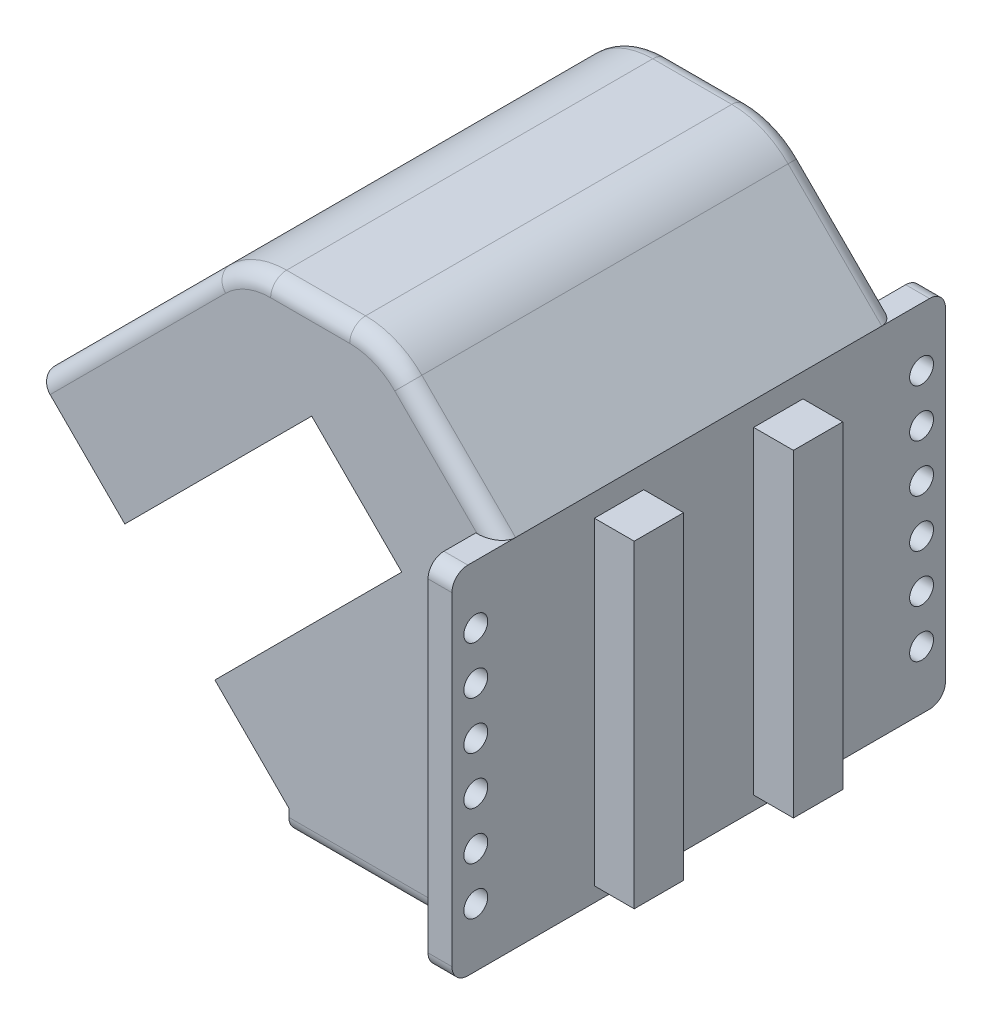
SolidWorks part; units mm, degrees
ref_plane "前视基准面" through (0, 0, 0) normal (0, 0, 1) x (1, 0, 0)
ref_plane "上视基准面" through (0, 0, 0) normal (0, 1, 0) x (1, 0, 0)
ref_plane "右视基准面" through (0, 0, 0) normal (1, 0, 0) x (0, 0, -1)
sketch "草图1" plane through (0, 0, 0) normal (0, 0, 1) x (1, 0, 0)
  line L5 (25.716, 61.2098) -> (43.9292, 61.2098)
  line L7 (32.1507, 1.8232) -> (58.6267, 1.8232)
  line L12 (58.6267, 46.5123) -> (58.6267, 1.8232)
  line L13 (25.716, 58.2098) -> (55.6267, 28.2991)
  line L14 (55.6267, 28.2991) -> (32.1507, 4.8232)
  line L17 (32.1507, 4.8232) -> (32.1507, 1.8232)
  line L18 (25.716, 58.2098) -> (25.716, 61.2098)
  line L19 (43.9292, 61.2098) -> (58.6267, 46.5123)
  line L20 (36.3226, 68.8164) -> (66.2333, 38.9057) construction
  dimension "D1" = 15
  dimension "D2" = 42.3
  dimension "D3" = 3
  dimension "D4" = 3
  dimension "D5" = 3
  dimension "D6" = 45
extrude "凸台-拉伸1" add sketch "草图1" along normal blind 50
sketch "草图3" plane through (41.9629, 41.9629, 0) normal (-0.7071, -0.7071, 0) x (0, 0, 1)
  line L0 (50, -19.3235) -> (46.15, -19.3235)
  line L1 (50, 22.9765) -> (50, -19.3235)
  line L2 (50, 22.9765) -> (46.15, 22.9765)
  line L3 (0, 22.9765) -> (0, -19.3235)
  line L4 (3.85, 19.9765) -> (3.85, -16.3235)
  line L5 (46.15, 19.9765) -> (46.15, -16.3235)
  line L6 (3.85, 22.9765) -> (0, 22.9765)
  line L7 (3.85, -19.3235) -> (0, -19.3235)
  line L8 (3.85, 19.9765) -> (6.85, 22.9765)
  line L9 (6.85, 22.9765) -> (3.85, 22.9765)
  line L10 (-6.5065, 1.8265) -> (10.2722, 1.8265) construction
  line L11 (6.85, -19.3235) -> (3.85, -19.3235)
  line L12 (3.85, -16.3235) -> (6.85, -19.3235)
  line L13 (25, 22.9765) -> (25, 16.7337) construction
  line L14 (43.15, -19.3235) -> (46.15, -19.3235)
  line L15 (46.15, -16.3235) -> (43.15, -19.3235)
  line L16 (43.15, 22.9765) -> (46.15, 22.9765)
  line L17 (46.15, 19.9765) -> (43.15, 22.9765)
  point P0 (0, 22.9765)
  dimension "D1" = 42.3
  dimension "D2" = 3
  dimension "D3" = 45
extrude "凸台-拉伸3" add sketch "草图3" along normal up to vertex (33.2 mm away) up to point (32.1507, 4.8232, 0)
sketch "草图4" plane through (18.487, 18.487, 0) normal (-0.7071, -0.7071, 0) x (0, 0, 1)
  line L1 (0, 25.0978) -> (50, 25.0978)
  line L2 (0, 25.0978) -> (0, 22.9765)
  line L3 (0, 22.9765) -> (50, 22.9765)
  line L4 (50, 25.0978) -> (50, 22.9765)
extrude "凸台-拉伸4" add sketch "草图4" against normal up to vertex
sketch "草图5" plane through (0, 0, 0) normal (0, 0, -1) x (-1, 0, 0)
  line L0 (-35.0145, 48.9113) -> (-46.3282, 37.5976)
  line L1 (-46.3282, 37.5976) -> (-22.8523, 14.1217)
  line L2 (-0.7401, 36.2338) -> (-32.1507, 4.8232) construction
  line L3 (-22.8523, 14.1217) -> (-11.5386, 25.4354)
  line L4 (-11.5386, 25.4354) -> (-35.0145, 48.9113)
  line L5 (-27.8374, 56.0884) -> (-53.5053, 30.4205) construction
extrude "切除-拉伸1" cut sketch "草图5" against normal through all
sketch "草图8" plane through (58.6267, 0, 0) normal (1, 0, 0) x (0, 0, -1)
  line L5 (-56, 46.5123) -> (6, 46.5123)
  line L7 (-25, 64.5937) -> (-25, -13.8029) construction
  line L8 (6, -4.1768) -> (6, 52.5123)
  line L9 (6, 52.5123) -> (-56, 52.5123)
  line L10 (-56, 52.5123) -> (-56, -4.1768)
  line L11 (-56, -4.1768) -> (6, -4.1768)
  line L12 (6, 1.8232) -> (6, 46.5123)
  line L14 (-56, 46.5123) -> (-56, 1.8232)
  line L16 (-56, 1.8232) -> (6, 1.8232)
  circle A0 centre (-53, 39.1623) radius 1.5
  circle A2 centre (-53, 33.1623) radius 1.5
  circle A3 centre (-53, 27.1623) radius 1.5
  circle A4 centre (-53, 21.1623) radius 1.5
  circle A5 centre (-53, 15.1623) radius 1.5
  circle A6 centre (-53, 9.1623) radius 1.5
  circle A7 centre (3, 9.1623) radius 1.5
  circle A8 centre (3, 15.1623) radius 1.5
  circle A9 centre (3, 21.1623) radius 1.5
  circle A10 centre (3, 27.1623) radius 1.5
  circle A11 centre (3, 33.1623) radius 1.5
  circle A12 centre (3, 39.1623) radius 1.5
  dimension "D2" = 3
  dimension "D3" = 3
  dimension "D4" = 6
  dimension "D5" = 7.35
  dimension "D1" = 6
extrude "凸台-拉伸5" add sketch "草图8" against normal blind 3
fillet "圆角1" radius 10 2 edges at (43.9292, 61.2098, 25) (25.716, 61.2098, 25)
fillet "圆角2" radius 2 16 edges at (52.7424, 52.3966, 0) (52.7424, 52.3966, 50) (43.6139, 60.4486, 50) (43.6139, 60.4486, 0) (34.8226, 61.2098, 50) (34.8226, 61.2098, 0) (26.0313, 60.4486, 50) (26.0313, 60.4486, 0) (11.7636, 47.2573, 0) (11.7636, 47.2573, 50) (57.1267, 1.8232, 56) (43.8887, 1.8232, 50) (43.8887, 1.8232, 0) (57.1267, 1.8232, -6) (57.1267, 46.5123, -6) (57.1267, 46.5123, 56)
sketch "草图9" plane through (58.6267, 0, 0) normal (1, 0, 0) x (0, 0, -1)
  line L1 (-38.0974, 43.6582) -> (-31.8974, 43.6582)
  line L2 (-38.0974, 43.6582) -> (-38.0974, 3.6582)
  line L3 (-38.0974, 3.6582) -> (-31.8974, 3.6582)
  line L4 (-31.8974, 43.6582) -> (-31.8974, 3.6582)
  dimension "D1" = 40
  dimension "D2" = 6.2
sketch "草图10" plane through (58.6267, 0, 0) normal (1, 0, 0) x (0, 0, -1)
  line L1 (-18.0978, 43.5412) -> (-11.8978, 43.5412)
  line L2 (-18.0978, 43.5412) -> (-18.0978, 3.5412)
  line L3 (-18.0978, 3.5412) -> (-11.8978, 3.5412)
  line L4 (-11.8978, 43.5412) -> (-11.8978, 3.5412)
  point P4 (-79.055, 50.7902)
  dimension "D1" = 40
  dimension "D2" = 6.2
extrude "凸台-拉伸6" add sketch "草图9" along normal blind 5
extrude "凸台-拉伸7" add sketch "草图10" along normal blind 5
